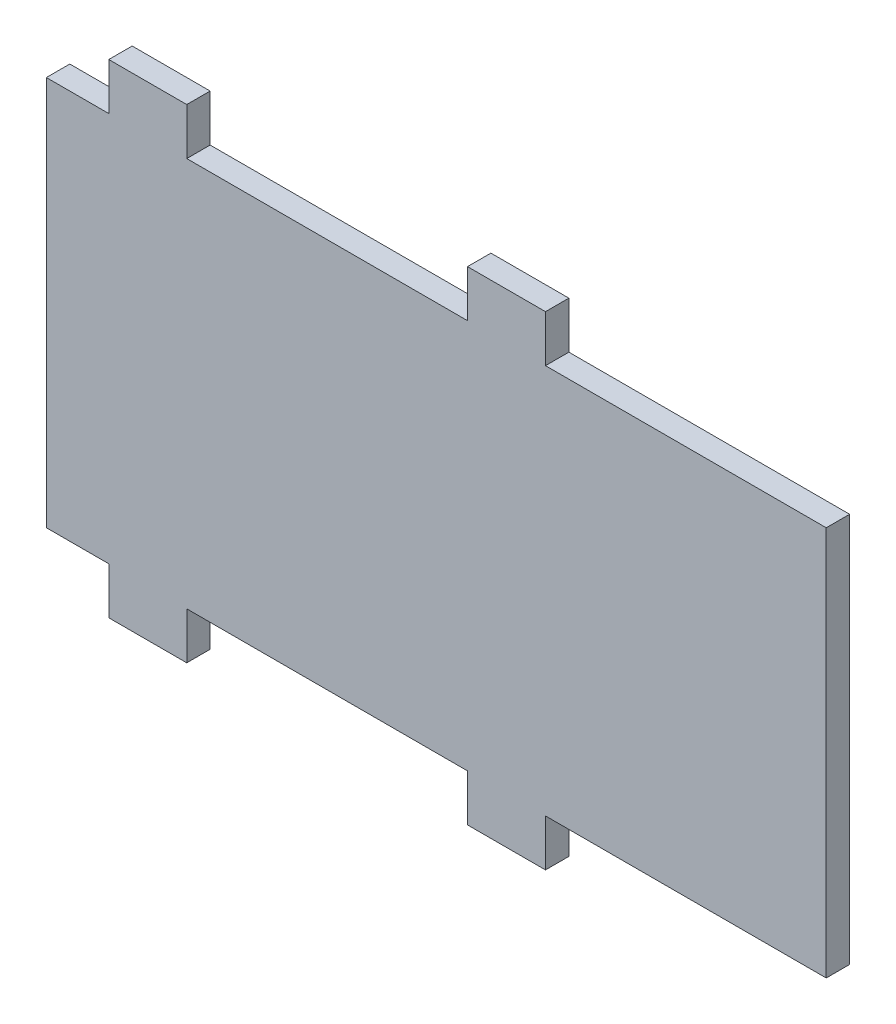
SolidWorks part; units mm, degrees
ref_plane "Plan de face" through (0, 0, 0) normal (0, 0, 1) x (1, 0, 0)
ref_plane "Plan de dessus" through (0, 0, 0) normal (0, 1, 0) x (1, 0, 0)
ref_plane "Plan de droite" through (0, 0, 0) normal (1, 0, 0) x (0, 0, -1)
sketch "Esquisse1" plane through (0, 0, 0) normal (0, 0, 1) x (1, 0, 0)
  line L1 (0, 0) -> (-100, 0)
  line L2 (0, 0) -> (0, 62)
  line L3 (-100, 62) -> (0, 62)
  line L4 (-100, 0) -> (-100, 62)
  dimension "D1" = 62
  dimension "D2" = 100
extrude "Boss.-Extru.1" add sketch "Esquisse1" along normal blind 3
sketch "Esquisse2" plane through (0, 0, 3) normal (0, 0, 1) x (1, 0, 0)
  line L0 (-100, 0) -> (0, 0) construction
  line L1 (-100, 0) -> (-92, 0)
  line L2 (-100, 0) -> (-100, 6)
  line L3 (-100, 6) -> (-92, 6)
  line L4 (-92, 0) -> (-92, 6)
  line L5 (-82, 0) -> (-46, 0)
  line L6 (-82, 0) -> (-82, 6)
  line L7 (-82, 6) -> (-46, 6)
  line L8 (-46, 0) -> (-46, 6)
  line L9 (0, 0) -> (0, 62) construction
  line L10 (-36, 0) -> (0, 0)
  line L11 (-36, 0) -> (-36, 6)
  line L12 (-36, 6) -> (0, 6)
  line L13 (0, 0) -> (0, 6)
  line L14 (-128, 31) -> (0, 31) construction
  line L16 (0, 62) -> (0, 56)
  line L17 (-36, 56) -> (0, 56)
  line L18 (-36, 62) -> (-36, 56)
  line L19 (-36, 62) -> (0, 62)
  line L20 (-46, 62) -> (-46, 56)
  line L21 (-82, 56) -> (-46, 56)
  line L22 (-82, 62) -> (-82, 56)
  line L23 (-82, 62) -> (-46, 62)
  line L24 (-92, 62) -> (-92, 56)
  line L25 (-100, 56) -> (-92, 56)
  line L26 (-100, 62) -> (-100, 56)
  line L27 (-100, 62) -> (-92, 62)
  dimension "D1" = 10
  dimension "D2" = 10
  dimension "D3" = 36
  dimension "D4" = 36
  dimension "D5" = 6
  dimension "D6" = 6
  dimension "D7" = 6
extrude "Enlèv. mat.-Extru.1" cut sketch "Esquisse2" against normal blind 3
